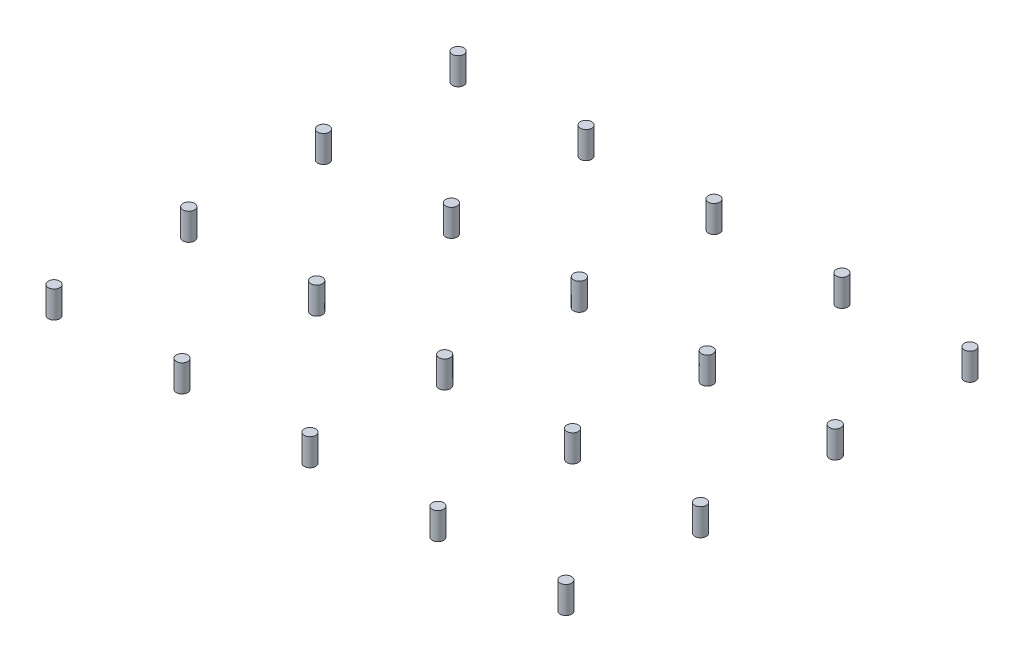
SolidWorks part; units mm, degrees
ref_plane "Front Plane" through (0, 0, 0) normal (0, 0, 1) x (1, 0, 0)
ref_plane "Top Plane" through (0, 0, 0) normal (0, 1, 0) x (1, 0, 0)
ref_plane "Right Plane" through (0, 0, 0) normal (1, 0, 0) x (0, 0, -1)
sketch "Sketch3" plane through (0, 0, 0) normal (0, 1, 0) x (1, 0, 0)
  circle A0 centre (-39, 5) radius 0.425
  circle A1 centre (-29.5, 5) radius 0.425
  circle A2 centre (-20, 5) radius 0.425
  circle A3 centre (-10.5, 5) radius 0.425
  circle A4 centre (-1, 5) radius 0.425
  circle A5 centre (-29.5, 15) radius 0.425
  circle A6 centre (-20, 15) radius 0.425
  circle A7 centre (-10.5, 15) radius 0.425
  circle A8 centre (-1, 15) radius 0.425
  circle A9 centre (-29.5, 25) radius 0.425
  circle A10 centre (-20, 25) radius 0.425
  circle A11 centre (-10.5, 25) radius 0.425
  circle A12 centre (-1, 25) radius 0.425
  circle A13 centre (-29.5, 35) radius 0.425
  circle A14 centre (-20, 35) radius 0.425
  circle A15 centre (-10.5, 35) radius 0.425
  circle A16 centre (-1, 35) radius 0.425
  circle A17 centre (-39, 15) radius 0.425
  circle A18 centre (-39, 25) radius 0.425
  circle A19 centre (-39, 35) radius 0.425
  dimension "D9" = 0.85
  dimension "D12" = 5
  dimension "D13" = 4
extrude "Boss-Extrude1" add sketch "Sketch3" along normal blind 2
